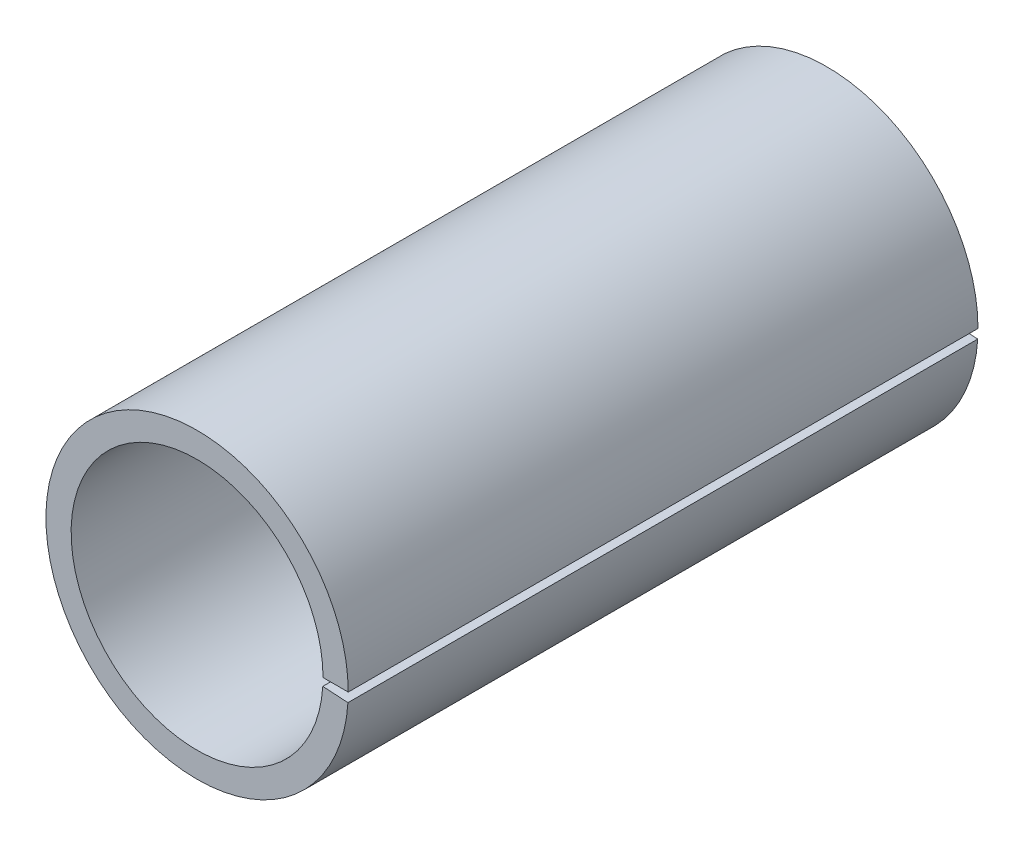
SolidWorks part; units mm, degrees
ref_plane "前视基准面" through (0, 0, 0) normal (0, 0, 1) x (1, 0, 0)
ref_plane "上视基准面" through (0, 0, 0) normal (0, 1, 0) x (1, 0, 0)
ref_plane "右视基准面" through (0, 0, 0) normal (1, 0, 0) x (0, 0, -1)
sketch "草图1" plane through (0, 0, 0) normal (0, 0, 1) x (1, 0, 0)
  circle A0 centre (0, 0) radius 5
  circle A1 centre (0, 0) radius 6
  dimension "D1" = 12
  dimension "D2" = 10
extrude "凸台-拉伸1" add sketch "草图1" along normal blind 25
sketch "草图2" plane through (0, 0, 25) normal (0, 0, 1) x (1, 0, 0)
  line L0 (0, 0) -> (6, 0)
  line L1 (0, 0) -> (5.9887, -0.3688)
  circle A0 centre (0, 0) radius 6 construction
  arc A1 (6, 0) -> (5.9887, -0.3688) centre (0, 0) cw
extrude "切除-拉伸1" cut sketch "草图2" against normal blind 30
